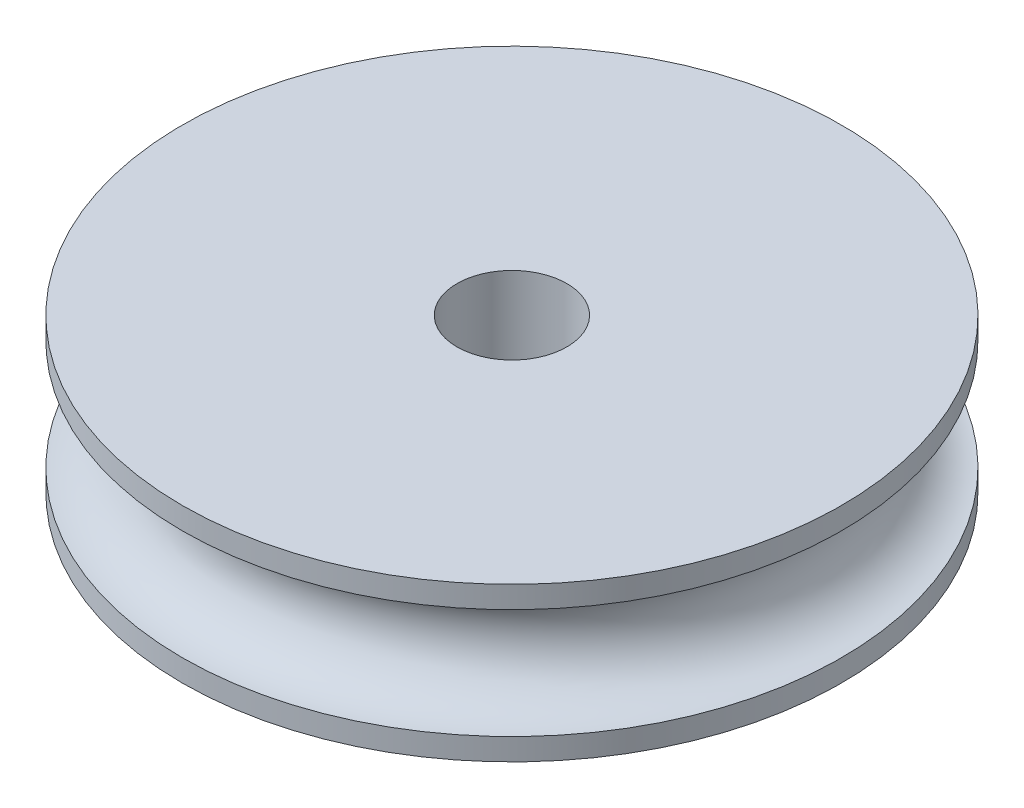
SolidWorks part; units mm, degrees
ref_plane "Front Plane" through (0, 0, 0) normal (0, 0, 1) x (1, 0, 0)
ref_plane "Top Plane" through (0, 0, 0) normal (0, 1, 0) x (1, 0, 0)
ref_plane "Right Plane" through (0, 0, 0) normal (1, 0, 0) x (0, 0, -1)
sketch "Sketch1" plane through (0, 0, 0) normal (1, 0, 0) x (0, 0, -1)
  line L0 (0, 4.445) -> (19.05, 4.445)
  line L1 (0, -3.175) -> (19.05, -3.175) construction
  line L2 (0, 4.445) -> (0, -4.445) construction
  line L3 (0, 3.175) -> (19.05, 3.175) construction
  line L4 (-13.8326, -4.445) -> (20.32, -4.445) construction
  line L5 (19.05, 3.175) -> (19.05, 4.445)
  line L6 (19.05, 3.175) -> (19.05, -3.175) construction
  line L7 (19.05, -3.175) -> (19.05, -4.445)
  line L8 (0, -4.445) -> (19.05, -4.445)
  line L9 (0, 4.445) -> (0, -4.445)
  line L10 (-12.5626, -3.175) -> (-12.5626, 3.175) construction
  line L11 (19.05, -3.175) -> (19.05, 3.175) construction
  line L12 (-12.5626, -3.175) -> (19.05, -3.175) construction
  line L13 (0, 0) -> (19.05, 3.175) construction
  line L14 (0, 0) -> (19.05, -3.175) construction
  line L15 (-12.5626, 3.175) -> (19.05, 3.175) construction
  line L16 (-13.8326, 4.445) -> (20.32, 4.445) construction
  line L17 (-13.8326, -4.445) -> (-13.8326, 4.445) construction
  line L18 (20.32, -4.445) -> (20.32, 4.445) construction
  arc A0 (19.05, 3.175) -> (19.05, -3.175) centre (19.05, 0) ccw
  dimension "D2" = 6.35
  dimension "D3" = 19.05
  dimension "D1" = 1.27
revolve "Revolve1" add sketch "Sketch1" angle 360 about L9
sketch "Sketch2" plane through (0, 4.445, 0) normal (0, 1, 0) x (1, 0, 0)
  circle A0 centre (0, 0) radius 3.175
  dimension "D1" = 6.35
extrude "Cut-Extrude1" cut sketch "Sketch2" against normal through all
